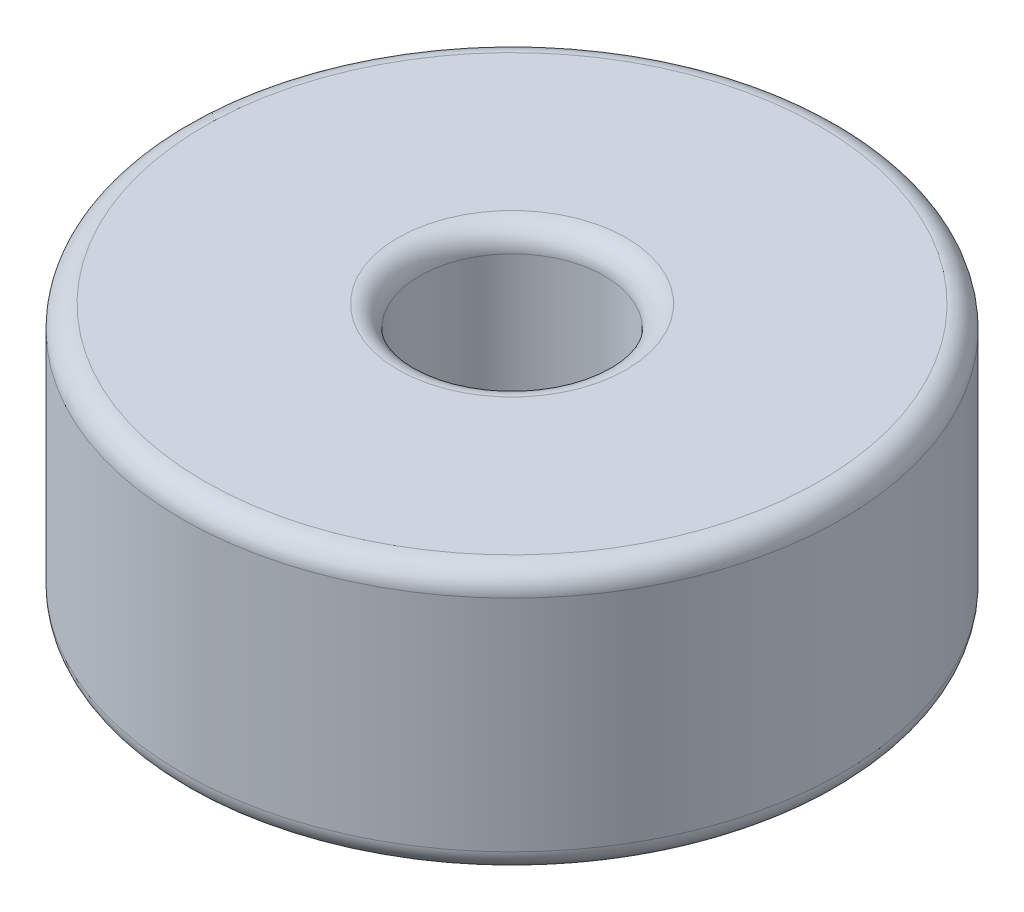
SolidWorks part; units mm, degrees
ref_plane "Front Plane" through (0, 0, 0) normal (0, 0, 1) x (1, 0, 0)
ref_plane "Top Plane" through (0, 0, 0) normal (0, 1, 0) x (1, 0, 0)
ref_plane "Right Plane" through (0, 0, 0) normal (1, 0, 0) x (0, 0, -1)
sketch "Sketch1" plane through (0, 0, 0) normal (0, 1, 0) x (1, 0, 0)
  circle A0 centre (0, 0) radius 7.5
  circle A1 centre (0, 0) radius 2.1
  dimension "D1" = 15
  dimension "D2" = 4.2
extrude "Boss-Extrude1" add sketch "Sketch1" along normal blind 6
fillet "Fillet1" radius 0.5 4 edges at (0, 0, 7.5) (0, 6, 7.5) (0, 0, 2.1) (0, 6, 2.1)
